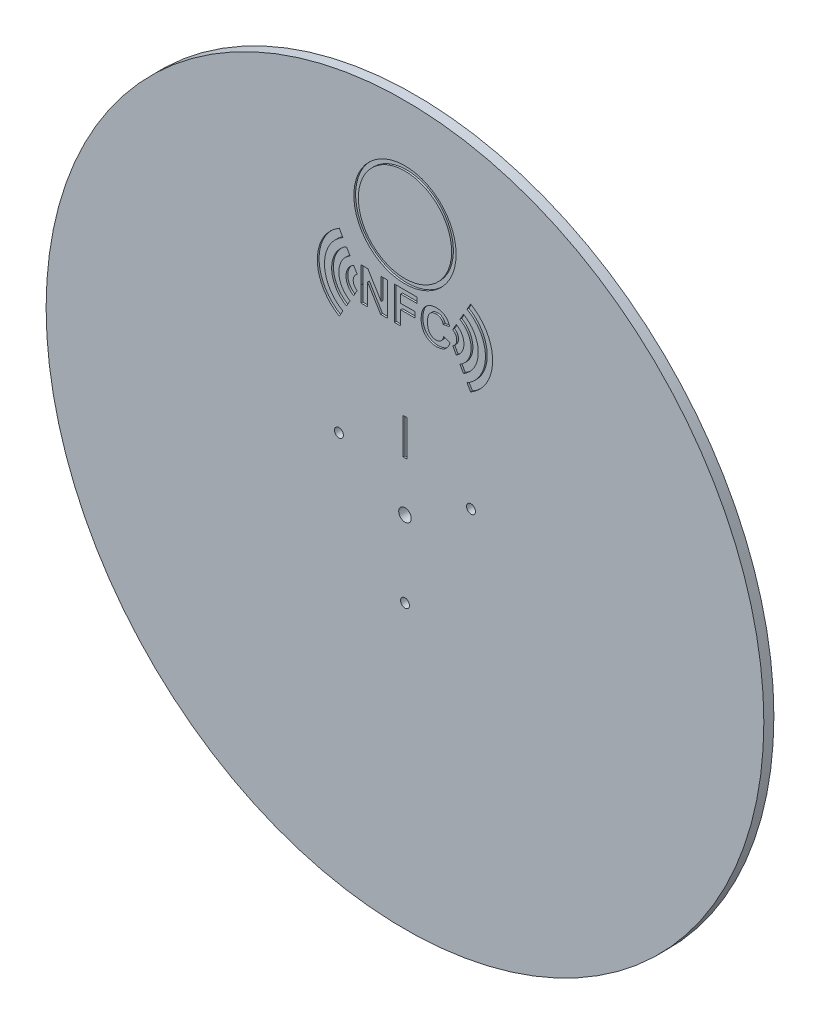
SolidWorks part; units mm, degrees
ref_plane "Front Plane" through (0, 0, 0) normal (0, 0, 1) x (1, 0, 0)
ref_plane "Top Plane" through (0, 0, 0) normal (0, 1, 0) x (1, 0, 0)
ref_plane "Right Plane" through (0, 0, 0) normal (1, 0, 0) x (0, 0, -1)
sketch "Sketch1" plane through (0, 0, 0) normal (0, 0, 1) x (1, 0, 0)
  circle A0 centre (0, 0) radius 100
  circle A1 centre (0, 70) radius 12.6
  circle A2 centre (0, 0) radius 1.75
  dimension "D1" = 25.2
  dimension "D3" = 200
  dimension "D4" = 3.5
  dimension "D2" = 70
extrude "Boss-Extrude1" add sketch "Sketch1" along normal blind 1.2
sketch "Sketch2" plane through (0, 0, 1.2) normal (0, 0, 1) x (1, 0, 0)
  circle A0 centre (0, 0) radius 100
  circle A1 centre (0, 0) radius 1.75
  circle A2 centre (0, 0) radius 1.75 construction
  circle A3 centre (0, 0) radius 100 construction
extrude "Boss-Extrude2" add sketch "Sketch2" along normal blind 0.8
sketch "Sketch3" plane through (0, 0, 2) normal (0, 0, 1) x (1, 0, 0)
  line L0 (-16.9706, 45) -> (16.9706, 45) construction
  line L1 (-12.1796, 49.417) -> (-22.0752, 32.2773)
  line L2 (-12.1796, 49.417) -> (-26.9014, 74.9159)
  line L3 (-12.1796, 49.417) -> (22.1968, 49.417) construction
  line L4 (0, 70) -> (0, 45) construction
  line L5 (12.1796, 49.417) -> (22.0752, 32.2773)
  line L6 (12.1796, 49.417) -> (26.9014, 74.9159)
  line L7 (-12.2094, 45) -> (-12.2094, 54.2459)
  line L8 (-12.2094, 54.2459) -> (-10.3517, 54.2459)
  line L9 (-10.3517, 54.2459) -> (-6.6381, 48.1672)
  line L10 (-6.6381, 48.1672) -> (-6.6381, 54.2459)
  line L11 (-6.6381, 54.2459) -> (-4.86, 54.2459)
  line L12 (-4.86, 54.2459) -> (-4.86, 45)
  line L13 (-4.86, 45) -> (-6.7752, 45)
  line L14 (-6.7752, 45) -> (-10.4313, 50.9825)
  line L15 (-10.4313, 50.9825) -> (-10.4313, 45)
  line L16 (-10.4313, 45) -> (-12.2094, 45)
  line L17 (-2.9634, 45) -> (-2.9634, 54.2459)
  line L18 (-2.9634, 54.2459) -> (3.3191, 54.2459)
  line L19 (3.3191, 54.2459) -> (3.3191, 52.705)
  line L20 (3.3191, 52.705) -> (-1.1854, 52.705)
  line L21 (-1.1854, 52.705) -> (-1.1854, 50.4527)
  line L22 (-1.1854, 50.4527) -> (2.7264, 50.4527)
  line L23 (2.7264, 50.4527) -> (2.7264, 48.9117)
  line L24 (2.7264, 48.9117) -> (-1.1854, 48.9117)
  line L25 (-1.1854, 48.9117) -> (-1.1854, 45)
  line L26 (-1.1854, 45) -> (-2.9634, 45)
  line L27 (10.7869, 48.4376) -> (12.565, 47.8449)
  line L28 (12.4465, 51.6381) -> (10.6684, 51.2825)
  arc A0 (-13.3046, 51.3655) -> (-13.3046, 47.4684) centre (-12.1796, 49.417) ccw
  arc A1 (-14.3046, 53.0976) -> (-14.3046, 45.7364) centre (-12.1796, 49.417) ccw
  arc A2 (-15.3046, 54.8296) -> (-15.3046, 44.0043) centre (-12.1796, 49.417) ccw
  arc A3 (-16.3046, 56.5617) -> (-16.3046, 42.2723) centre (-12.1796, 49.417) ccw
  arc A4 (-17.3046, 58.2938) -> (-17.3046, 40.5402) centre (-12.1796, 49.417) ccw
  arc A5 (-18.3046, 60.0258) -> (-18.3046, 38.8082) centre (-12.1796, 49.417) ccw
  arc A6 (18.3046, 60.0258) -> (18.3046, 38.8082) centre (12.1796, 49.417) cw
  arc A7 (17.3046, 58.2938) -> (17.3046, 40.5402) centre (12.1796, 49.417) cw
  arc A8 (16.3046, 56.5617) -> (16.3046, 42.2723) centre (12.1796, 49.417) cw
  arc A9 (15.3046, 54.8296) -> (15.3046, 44.0043) centre (12.1796, 49.417) cw
  arc A10 (14.3046, 53.0976) -> (14.3046, 45.7364) centre (12.1796, 49.417) cw
  arc A11 (13.3046, 51.3655) -> (13.3046, 47.4684) centre (12.1796, 49.417) cw
  circle A12 centre (0, 70) radius 13
  circle A13 centre (0, 70) radius 14.25
  spline S0 degree 3 poles (12.565, 47.8449) (12.4974, 47.6159) (12.3822, 47.2824) (12.1795, 46.8696) (12.0177, 46.5867) (11.8325, 46.3316) (11.6342, 46.0958) (11.4171, 45.8842) (11.1821, 45.6965) (10.9316, 45.5304) (10.6626, 45.39) (10.3792, 45.2691) (10.0784, 45.1711) (9.7623, 45.0928) (9.3091, 45.0218) (8.9596, 44.9989) (8.7218, 45) knots 0 0 0 0 0.137895 0.202903 0.265168 0.325675 0.384566 0.442764 0.500294 0.557901 0.61591 0.675133 0.73552 0.798252 0.862854 1 1 1 1
  spline S1 degree 3 poles (8.7218, 45) (8.4264, 44.998) (7.9903, 45.0359) (7.432, 45.1668) (7.04, 45.2995) (6.6702, 45.4756) (6.3195, 45.6874) (5.9903, 45.9395) (5.6838, 46.2275) (5.4053, 46.5492) (5.1645, 46.9029) (4.9587, 47.2836) (4.7924, 47.6932) (4.6625, 48.1311) (4.5373, 48.7675) (4.5042, 49.2644) (4.5044, 49.6026) knots 0 0 0 0 0.126019 0.185825 0.244304 0.302279 0.360196 0.418835 0.478842 0.539358 0.600002 0.661055 0.723669 0.788261 0.855679 1 1 1 1
  spline S2 degree 3 poles (4.5044, 49.6026) (4.5038, 49.9594) (4.5381, 50.481) (4.6601, 51.15) (4.7902, 51.606) (4.9541, 52.0324) (5.1601, 52.4248) (5.3985, 52.7885) (5.6757, 53.1169) (5.9837, 53.4085) (6.3136, 53.6663) (6.6687, 53.8826) (7.047, 54.0595) (7.449, 54.1963) (8.0264, 54.3308) (8.4788, 54.3619) (8.7848, 54.3645) knots 0 0 0 0 0.147853 0.216063 0.281514 0.344147 0.40504 0.464872 0.524079 0.582725 0.640362 0.697329 0.754684 0.813113 0.873015 1 1 1 1
  spline S3 degree 3 poles (8.7848, 54.3645) (9.0521, 54.3617) (9.4475, 54.3377) (9.9527, 54.228) (10.3058, 54.1195) (10.6383, 53.9761) (11.0566, 53.7426) (11.3387, 53.5188) (11.5111, 53.3532) knots 0 0 0 0 0.269222 0.396222 0.51914 0.640112 0.759624 1 1 1 1
  spline S4 degree 3 poles (11.5111, 53.3532) (11.6189, 53.2521) (11.7654, 53.0814) (11.9392, 52.8317) (12.0623, 52.6256) (12.172, 52.401) (12.3112, 52.0744) (12.397, 51.8163) (12.4465, 51.6381) knots 0 0 0 0 0.223923 0.340367 0.461367 0.587913 0.71931 1 1 1 1
  spline S5 degree 3 poles (10.6684, 51.2825) (10.6412, 51.3981) (10.5879, 51.5656) (10.4942, 51.7774) (10.4086, 51.9218) (10.3176, 52.0603) (10.2099, 52.1868) (10.0924, 52.3047) (9.9641, 52.4126) (9.8267, 52.5084) (9.6827, 52.5946) (9.5296, 52.6649) (9.3694, 52.7219) (9.2028, 52.7695) (8.966, 52.8099) (8.7842, 52.8264) (8.6607, 52.8235) knots 0 0 0 0 0.129415 0.191523 0.252186 0.31235 0.372124 0.433096 0.493819 0.554747 0.61575 0.676633 0.738217 0.801142 0.865493 1 1 1 1
  spline S6 degree 3 poles (8.6607, 52.8235) (8.4915, 52.8261) (8.2426, 52.7998) (7.9226, 52.7271) (7.6997, 52.6461) (7.4907, 52.5424) (7.2933, 52.4163) (7.1085, 52.2684) (6.9362, 52.0969) (6.7816, 51.8988) (6.6457, 51.6735) (6.5329, 51.4187) (6.4414, 51.1366) (6.3694, 50.8268) (6.298, 50.3592) (6.2853, 49.9911) (6.2825, 49.7378) knots 0 0 0 0 0.114442 0.169048 0.221995 0.274768 0.326889 0.380477 0.434921 0.491257 0.55039 0.612762 0.67972 0.751074 0.828129 1 1 1 1
  spline S7 degree 3 poles (6.2825, 49.7378) (6.2853, 49.4703) (6.2976, 49.0825) (6.3696, 48.5897) (6.4407, 48.2649) (6.5327, 47.9706) (6.6452, 47.7074) (6.779, 47.475) (6.9339, 47.2735) (7.1059, 47.1004) (7.2903, 46.9516) (7.4862, 46.8243) (7.6946, 46.7196) (7.9163, 46.6405) (8.2331, 46.5621) (8.4813, 46.5399) (8.6496, 46.541) knots 0 0 0 0 0.177656 0.256733 0.330177 0.398063 0.460995 0.519731 0.575527 0.629114 0.681254 0.732498 0.783792 0.835623 0.888379 1 1 1 1
  spline S8 degree 3 poles (8.6496, 46.541) (8.7745, 46.5428) (8.9609, 46.5521) (9.2008, 46.6033) (9.3717, 46.6533) (9.5367, 46.7161) (9.6934, 46.7965) (9.8446, 46.889) (9.9874, 46.9974) (10.1237, 47.1191) (10.2479, 47.2597) (10.3632, 47.416) (10.468, 47.5888) (10.5658, 47.7768) (10.6801, 48.0588) (10.7505, 48.282) (10.7869, 48.4376) knots 0 0 0 0 0.120461 0.178741 0.235724 0.291792 0.348406 0.404979 0.462271 0.52076 0.580529 0.642578 0.707405 0.77492 0.84633 1 1 1 1
  point P3 (0, 45)
  dimension "D2" = 2
  dimension "D3" = 2
  dimension "D4" = 2
  dimension "D5" = 2
  dimension "D6" = 2
  dimension "D7" = 4.5
  dimension "D10" = 26
  dimension "D11" = 1.25
  dimension "D1" = 45
  dimension "D8" = 120
  dimension "D9" = 120
extrude "Cut-Extrude1" cut sketch "Sketch3" against normal blind 0.5 contours L16 L15 L14 L13 L12 L11 L10 L9 L8 L7 L2 L1 | L26 L25 L24 L23 L22 L21 L20 L19 L18 L17 | S8 S7 S6 S5 L28 S4 S3 S2 S1 S0 L27 | L6 A11 L5 A10 | L6 A9 L5 A8 | L6 A7 L5 A6 | L2 A1 L1 A0 | L2 A3 L1 A2 | L2 A5 L1 A4 | A13 | A12
sketch "Sketch4" plane through (0, 0, 0) normal (0, 0, -1) x (-1, 0, 0)
  circle A0 centre (0, 0) radius 100
  circle A1 centre (0, 0) radius 1.75
  circle A2 centre (0, 0) radius 1.75 construction
  circle A3 centre (0, 0) radius 100 construction
extrude "Boss-Extrude3" add sketch "Sketch4" along normal blind 0.8
sketch "Sketch5" plane through (0, 0, 2) normal (0, 0, 1) x (1, 0, 0)
  line L1 (-0.5, 23.75) -> (0.5, 23.75)
  line L2 (-0.5, 23.75) -> (-0.5, 13.75)
  line L3 (-0.5, 13.75) -> (0.5, 13.75)
  line L4 (0.5, 23.75) -> (0.5, 13.75)
  circle A0 centre (0, -21.25) radius 1.25
  circle A1 centre (-18.403, 10.625) radius 1.25
  circle A2 centre (18.403, 10.625) radius 1.25
  circle A3 centre (0, 0) radius 1.75 construction
  point P14 (0, 0)
  dimension "D2" = 2.5
  dimension "D1" = 21.25
  dimension "D4" = 1
  dimension "D5" = 10
  dimension "D3" = 0.5
  dimension "D6" = 35
  dimension "D7" = 3
extrude "Cut-Extrude2" cut sketch "Sketch5" against normal up to surface (2.8 mm away) contours L2 L1 L4 L3 | A2 | A1 | A0 up to face at (-100, 0, -0.8)
sketch "Sketch6" plane through (0, 0, -0.8) normal (0, 0, -1) x (-1, 0, 0)
  line L1 (-0.5, 23.75) -> (0.5, 23.75)
  line L2 (-0.5, 23.75) -> (-0.5, 13.75)
  line L3 (-0.5, 13.75) -> (0.5, 13.75)
  line L4 (0.5, 23.75) -> (0.5, 13.75)
extrude "Boss-Extrude4" add sketch "Sketch6" against normal up to surface (2.3 mm away) up to face at (9.4165, 50.0138, 1.5)
